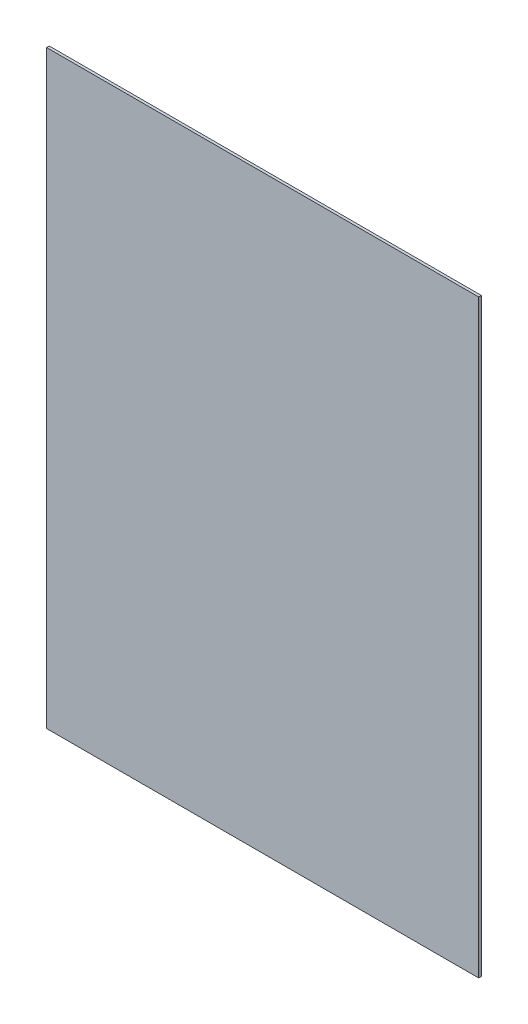
SolidWorks part; units mm, degrees
ref_plane "Front Plane" through (0, 0, 0) normal (0, 0, 1) x (1, 0, 0)
ref_plane "Top Plane" through (0, 0, 0) normal (0, 1, 0) x (1, 0, 0)
ref_plane "Right Plane" through (0, 0, 0) normal (1, 0, 0) x (0, 0, -1)
sketch "Sketch2" plane through (0, 0, 0) normal (0, 0, 1) x (1, 0, 0)
  line L1 (-165, 225.24) -> (165, 225.24)
  line L2 (-165, 225.24) -> (-165, -225.24)
  line L3 (-165, -225.24) -> (165, -225.24)
  line L4 (165, 225.24) -> (165, -225.24)
  line L5 (-165, 225.24) -> (165, -225.24) construction
  line L6 (-165, -225.24) -> (165, 225.24) construction
  point P0 (0, 0)
  dimension "Length 1" = 330
  dimension "Length 2" = 450.48
extrude "Boss-Extrude1" add sketch "Sketch2" along normal blind 2.032
sketch "Sketch3" [suppressed] plane through (0, 0, 2.032) normal (0, 0, 1) x (1, 0, 0)
  circle A0 centre (-175.117, 128.01) radius 3.1
  circle A1 centre (175.117, 128.01) radius 3.1
  circle A8 centre (-175.1171, -128.01) radius 3.1
  circle A9 centre (175.1169, -128.01) radius 3.1
  dimension "D1" = 6.2
extrude "Cut-Extrude1" [suppressed] cut sketch "Sketch3" against normal through all both and the other way through all
fillet "Fillet1" [suppressed] radius 10
sketch "Sketch4" [suppressed] plane through (0, 0, 0) normal (0, 0, -1) x (-1, 0, 0)
  circle A0 centre (-423.777, 128.01) radius 3.1
  circle A1 centre (423.777, 128.01) radius 3.1
  circle A2 centre (423.777, -128.01) radius 3.1
  circle A3 centre (-423.777, -128.01) radius 3.1
  dimension "D1" = 6.2
extrude "Cut-Extrude2" [suppressed] cut sketch "Sketch4" against normal through all both and the other way through all
fillet "Fillet2" [suppressed] radius 10
sketch "Sketch5" [suppressed] plane through (0, 0, 0) normal (0, 0, -1) x (-1, 0, 0)
  circle A0 centre (-175.117, -437.5) radius 3.1
  circle A1 centre (175.1169, -437.5) radius 3.1
  circle A2 centre (175.1169, 437.5) radius 3.1
  circle A3 centre (-175.117, 437.5) radius 3.1
  dimension "D1" = 6.2
extrude "Cut-Extrude3" [suppressed] cut sketch "Sketch5" against normal through all both and the other way through all
fillet "Fillet3" [suppressed] radius 10
